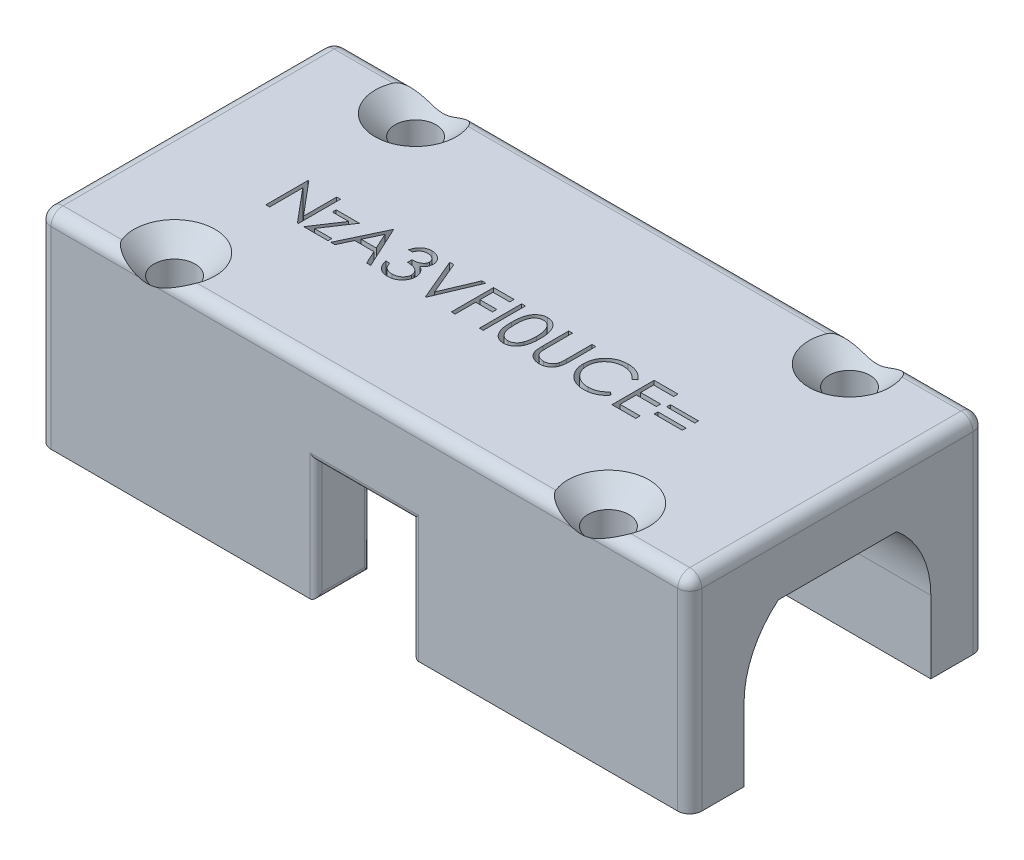
SolidWorks part; units mm, degrees
ref_plane "Alzado" through (0, 0, 0) normal (0, 0, 1) x (1, 0, 0)
ref_plane "Planta" through (0, 0, 0) normal (0, 1, 0) x (1, 0, 0)
ref_plane "Vista lateral" through (0, 0, 0) normal (1, 0, 0) x (0, 0, -1)
sketch "Croquis1" plane through (0, 0, 0) normal (0, 1, 0) x (1, 0, 0)
  line L1 (-27, 12.25) -> (27, 12.25)
  line L2 (-27, 12.25) -> (-27, -12.25)
  line L3 (-27, -12.25) -> (27, -12.25)
  line L4 (27, 12.25) -> (27, -12.25)
  line L5 (-27, 12.25) -> (27, -12.25) construction
  line L6 (-27, -12.25) -> (27, 12.25) construction
  point P0 (0, 0)
  dimension "D1" = 54
  dimension "D2" = 24.5
extrude "Saliente-Extruir1" add sketch "Croquis1" along normal blind 17
sketch "Croquis6" plane through (27, 0, 0) normal (1, 0, 0) x (0, 0, -1)
  line L0 (0, 0) -> (0, 12) construction
  line L1 (0, 12) -> (4.9054, 12)
  line L2 (0, 12) -> (-4.9054, 12)
  arc A0 (-4.9054, 12) -> (4.9054, 12) centre (0, 6) ccw
  dimension "D2" = 15.5
  dimension "D1" = 12
extrude "Cortar-Extruir3" cut sketch "Croquis6" against normal through all
sketch "Croquis7" plane through (0, 0, 12.25) normal (0, 0, 1) x (1, 0, 0)
  line L0 (0, 0) -> (0, 17) construction
  line L1 (-27, 17) -> (27, 17) construction
  line L2 (-27, 0) -> (27, 0) construction
  line L3 (-4, 10) -> (4, 10)
  line L4 (-4, 10) -> (-4, 0)
  line L5 (-4, 0) -> (4, 0)
  line L6 (4, 10) -> (4, 0)
  line L7 (-4, 10) -> (4, 0) construction
  line L8 (-4, 0) -> (4, 10) construction
  point P5 (0, 5)
  dimension "D1" = 10
  dimension "D2" = 8
extrude "Cortar-Extruir4" cut sketch "Croquis7" against normal blind 10
sketch "Croquis8" plane through (27, 0, 0) normal (1, 0, 0) x (0, 0, -1)
  line L0 (-4.9054, 0) -> (4.9054, 0) construction
  line L2 (-7.75, -6) -> (7.75, -6)
  line L3 (-7.75, -6) -> (-7.75, 6)
  line L4 (-7.75, 6) -> (7.75, 6)
  line L5 (7.75, -6) -> (7.75, 6)
  line L6 (-7.75, -6) -> (7.75, 6) construction
  line L7 (-7.75, 6) -> (7.75, -6) construction
  arc A0 (4.9054, 0) -> (4.9054, 12) centre (0, 6) ccw construction
  point P4 (0, 0)
extrude "Cortar-Extruir5" cut sketch "Croquis8" against normal through all
fillet "Redondeo1" radius 1 8 edges at (0, 17, 12.25) (-27, 17, 0) (0, 17, -12.25) (27, 17, 0) (-27, 8.5, 12.25) (-27, 8.5, -12.25) (27, 8.5, -12.25) (27, 8.5, 12.25)
sketch "Croquis9" plane through (0, 0, 0) normal (0, -1, 0) x (-1, 0, 0)
  line L0 (0, 12.25) -> (0, 0) construction
  line L1 (-26, 12.25) -> (26, 12.25) construction
  line L2 (0, 0) -> (27, 0) construction
  line L3 (27, 4.9054) -> (27, -4.9054) construction
  line L6 (26, -12.25) -> (4, -12.25) construction
  line L8 (27, -7.75) -> (27, -11.25) construction
  circle A0 centre (18, -10) radius 1
  circle A1 centre (9, -10) radius 1
  circle A2 centre (9, 10) radius 1
  circle A3 centre (18, 10) radius 1
  circle A4 centre (-9, 10) radius 1
  circle A5 centre (-18, 10) radius 1
  circle A6 centre (-9, -10) radius 1
  circle A7 centre (-18, -10) radius 1
  dimension "D1" = 2
  dimension "D2" = 2
  dimension "D3" = 2.25
  dimension "D4" = 2.25
  dimension "D5" = 9
  dimension "D6" = 9
sketch "Croquis14" plane through (0, 17, 0) normal (0, 1, 0) x (1, 0, 0)
  line L1 (0, 12.25) -> (0, 0) construction
  line L2 (0, 0) -> (-27, 0) construction
  circle A0 centre (-18, 10) radius 1.0126
  circle A1 centre (-9, 10) radius 1
  circle A2 centre (-9, -10) radius 1
  circle A3 centre (-18, -10) radius 1.0126
  circle A4 centre (9, -10) radius 1
  circle A5 centre (18, -10) radius 1.0126
  circle A6 centre (9, 10) radius 1
  circle A7 centre (18, 10) radius 1.0126
hole_wizard "Refrentado para tornillo tapón con cabeza plana de clavija de M31" positions "Croquis3D4" profile "Croquis16" countersink size "M3" standard "Ansi Metric" end condition through all
sketch3d "Croquis3D4"
  point P0 (-18, 17, -10)
  point P9 (18, 17, -10)
  point P12 (18, 17, 10)
  point P21 (-18, 17, 10)
sketch "Croquis16" plane through (-18, 17, -10) normal (1, 0, 0) x (0, 0, 1)
  line L0 (0, 0) -> (0, 17)
  line L1 (0, 17) -> (1.7, 17)
  line L2 (1.7, 17) -> (1.7, 1.66)
  line L3 (1.7, 1.66) -> (3.36, 0)
  line L5 (3.36, 0) -> (0, 0)
  line L6 (-1.7, 1.66) -> (-3.36, 0) construction
  line L11 (0, -6.35) -> (0, 107.95) construction
  dimension "Diámetro de taladro hasta el siguiente" = 3.4
  dimension "Profundidad de taladro hasta el siguiente" = 17
  dimension "Diámetro de avellanado cercano" = 6.72
  dimension "Ángulo de avellanado cercano" = 90
fillet "Fillet1" radius 0.5 9 edges at (4, 8.0759, 7.4668) (-4, 8.0759, 7.4668) (-4, 0, 10) (4, 0, 10) (4, 3, 7.75) (-4, 3, 7.75) (0, 10, 12.25) (4, 5, 12.25) (-4, 5, 12.25)
sketch "Croquis17" plane through (0, 0, -12.25) normal (0, 0, -1) x (-1, 0, 0)
  line L1 (-26, 16) -> (-26, 0) construction
  line L2 (26, 0) -> (26, 16) construction
  line L3 (0, 16) -> (0, 0) construction
  line L4 (17.2879, 16) -> (-17.2879, 16) construction
  line L6 (-26, 4.963) -> (26, 4.963) construction
sketch "Croquis18" plane through (0, 0, -12.25) normal (0, 0, -1) x (-1, 0, 0)
  line L0 (0, 16) -> (0, 0) construction
  line L5 (0, 8.8883) -> (0.5, 8.8883)
  line L7 (0, 7.8883) -> (0.5, 7.8883)
  line L8 (0.5, 8.8883) -> (0.5, 7.8883)
  line L10 (0, 8.8883) -> (-0.5, 8.8883)
  line L12 (0, 7.8883) -> (-0.5, 7.8883)
  line L13 (-0.5, 8.8883) -> (-0.5, 7.8883)
  line L14 (1.7, 8.8883) -> (1.7, 7.8883)
  line L31 (4.8, 8.8883) -> (5.3, 8.8883)
  line L33 (4.8, 7.8883) -> (5.3, 7.8883)
  line L34 (4.8, 7.8883) -> (4.3, 7.8883)
  line L35 (4.3, 8.8883) -> (4.3, 7.8883)
  line L36 (4.8, 8.8883) -> (4.3, 8.8883)
  line L43 (1.2, 10.0883) -> (1.7, 10.0883)
  line L44 (1.7, 10.0883) -> (1.7, 9.0883)
  line L45 (1.2, 9.0883) -> (1.7, 9.0883)
  line L46 (1.2, 9.0883) -> (0.7, 9.0883)
  line L47 (0.7, 10.0883) -> (0.7, 9.0883)
  line L48 (1.2, 10.0883) -> (0.7, 10.0883)
  line L49 (2.4, 10.0883) -> (2.9, 10.0883)
  line L50 (2.9, 10.0883) -> (2.9, 9.0883)
  line L51 (2.4, 9.0883) -> (2.9, 9.0883)
  line L52 (2.4, 9.0883) -> (1.9, 9.0883)
  line L53 (1.9, 10.0883) -> (1.9, 9.0883)
  line L54 (2.4, 10.0883) -> (1.9, 10.0883)
  line L55 (3.6, 10.0883) -> (4.1, 10.0883)
  line L56 (4.1, 10.0883) -> (4.1, 9.0883)
  line L57 (3.6, 9.0883) -> (4.1, 9.0883)
  line L58 (3.6, 9.0883) -> (3.1, 9.0883)
  line L59 (3.1, 10.0883) -> (3.1, 9.0883)
  line L60 (3.6, 10.0883) -> (3.1, 10.0883)
  line L79 (2.4, 11.2883) -> (2.9, 11.2883)
  line L80 (2.9, 11.2883) -> (2.9, 10.2883)
  line L81 (2.4, 10.2883) -> (2.9, 10.2883)
  line L82 (2.4, 10.2883) -> (1.9, 10.2883)
  line L83 (1.9, 11.2883) -> (1.9, 10.2883)
  line L84 (2.4, 11.2883) -> (1.9, 11.2883)
  line L115 (3.6, 12.4883) -> (4.1, 12.4883)
  line L116 (4.1, 12.4883) -> (4.1, 11.4883)
  line L117 (3.6, 11.4883) -> (4.1, 11.4883)
  line L118 (3.6, 11.4883) -> (3.1, 11.4883)
  line L119 (3.1, 12.4883) -> (3.1, 11.4883)
  line L120 (3.6, 12.4883) -> (3.1, 12.4883)
  line L194 (0.5, 10.0883) -> (0.5, 9.0883)
  line L195 (0, 9.0883) -> (0.5, 9.0883)
  line L196 (0, 9.0883) -> (-0.5, 9.0883)
  line L223 (-1.2, 8.8883) -> (-0.7, 8.8883)
  line L228 (-1.2, 8.8883) -> (-1.7, 8.8883)
  line L244 (-4.8, 7.8883) -> (-5.3, 7.8883)
  line L253 (-1.2, 10.0883) -> (-0.7, 10.0883)
  line L254 (-0.7, 10.0883) -> (-0.7, 9.0883)
  line L255 (-1.2, 9.0883) -> (-0.7, 9.0883)
  line L256 (-1.2, 9.0883) -> (-1.7, 9.0883)
  line L257 (-1.7, 10.0883) -> (-1.7, 9.0883)
  line L258 (-1.2, 10.0883) -> (-1.7, 10.0883)
  line L259 (-2.4, 10.0883) -> (-1.9, 10.0883)
  line L260 (-1.9, 10.0883) -> (-1.9, 9.0883)
  line L261 (-2.4, 9.0883) -> (-1.9, 9.0883)
  line L262 (-2.4, 9.0883) -> (-2.9, 9.0883)
  line L263 (-2.9, 10.0883) -> (-2.9, 9.0883)
  line L264 (-2.4, 10.0883) -> (-2.9, 10.0883)
  line L265 (-3.6, 10.0883) -> (-3.1, 10.0883)
  line L266 (-3.1, 10.0883) -> (-3.1, 9.0883)
  line L267 (-3.6, 9.0883) -> (-3.1, 9.0883)
  line L268 (-3.6, 9.0883) -> (-4.1, 9.0883)
  line L269 (-4.1, 10.0883) -> (-4.1, 9.0883)
  line L270 (-3.6, 10.0883) -> (-4.1, 10.0883)
  line L289 (-2.4, 11.2883) -> (-1.9, 11.2883)
  line L290 (-1.9, 11.2883) -> (-1.9, 10.2883)
  line L291 (-2.4, 10.2883) -> (-1.9, 10.2883)
  line L292 (-2.4, 10.2883) -> (-2.9, 10.2883)
  line L293 (-2.9, 11.2883) -> (-2.9, 10.2883)
  line L294 (-2.4, 11.2883) -> (-2.9, 11.2883)
  line L325 (-3.6, 12.4883) -> (-3.1, 12.4883)
  line L326 (-3.1, 12.4883) -> (-3.1, 11.4883)
  line L327 (-3.6, 11.4883) -> (-3.1, 11.4883)
  line L328 (-3.6, 11.4883) -> (-4.1, 11.4883)
  line L329 (-4.1, 12.4883) -> (-4.1, 11.4883)
  line L330 (-3.6, 12.4883) -> (-4.1, 12.4883)
  line L403 (0, 10.0883) -> (0.5, 10.0883)
  line L404 (0.5, 10.0883) -> (0.5, 9.0883)
  line L405 (0, 9.0883) -> (0.5, 9.0883)
  line L406 (0, 9.0883) -> (-0.5, 9.0883)
  line L407 (-0.5, 10.0883) -> (-0.5, 9.0883)
  line L408 (0, 10.0883) -> (-0.5, 10.0883)
  line L434 (1.2, 8.8883) -> (1.7, 8.8883)
  line L435 (1.7, 8.8883) -> (1.7, 7.8883)
  line L436 (1.2, 7.8883) -> (1.7, 7.8883)
  line L437 (1.2, 7.8883) -> (0.7, 7.8883)
  line L438 (0.7, 8.8883) -> (0.7, 7.8883)
  line L439 (1.2, 8.8883) -> (0.7, 8.8883)
  line L440 (3.1, 8.8883) -> (3.1, 7.8883)
  line L447 (4.3, 8.8883) -> (4.3, 7.8883)
  line L448 (3.6, 8.8883) -> (4.1, 8.8883)
  line L449 (4.1, 8.8883) -> (4.1, 7.8883)
  line L450 (3.6, 7.8883) -> (4.1, 7.8883)
  line L451 (3.6, 7.8883) -> (3.1, 7.8883)
  line L452 (3.1, 8.8883) -> (3.1, 7.8883)
  line L453 (3.6, 8.8883) -> (3.1, 8.8883)
  line L455 (4.8, 8.8883) -> (5.3, 8.8883)
  line L456 (5.3, 8.8883) -> (5.3, 7.8883)
  line L457 (4.8, 7.8883) -> (5.3, 7.8883)
  line L458 (4.8, 7.8883) -> (4.3, 7.8883)
  line L459 (4.3, 8.8883) -> (4.3, 7.8883)
  line L460 (4.8, 8.8883) -> (4.3, 8.8883)
  line L468 (1.9, 7.6883) -> (1.9, 6.6883)
  line L469 (1.2, 7.6883) -> (1.7, 7.6883)
  line L470 (1.7, 7.6883) -> (1.7, 6.6883)
  line L471 (1.2, 6.6883) -> (1.7, 6.6883)
  line L472 (1.2, 6.6883) -> (0.7, 6.6883)
  line L473 (0.7, 7.6883) -> (0.7, 6.6883)
  line L474 (1.2, 7.6883) -> (0.7, 7.6883)
  line L475 (3.1, 7.6883) -> (3.1, 6.6883)
  line L476 (2.4, 7.6883) -> (2.9, 7.6883)
  line L477 (2.9, 7.6883) -> (2.9, 6.6883)
  line L478 (2.4, 6.6883) -> (2.9, 6.6883)
  line L479 (2.4, 6.6883) -> (1.9, 6.6883)
  line L480 (1.9, 7.6883) -> (1.9, 6.6883)
  line L481 (2.4, 7.6883) -> (1.9, 7.6883)
  line L482 (4.3, 7.6883) -> (4.3, 6.6883)
  line L483 (3.6, 7.6883) -> (4.1, 7.6883)
  line L484 (4.1, 7.6883) -> (4.1, 6.6883)
  line L485 (3.6, 6.6883) -> (4.1, 6.6883)
  line L486 (3.6, 6.6883) -> (3.1, 6.6883)
  line L487 (3.1, 7.6883) -> (3.1, 6.6883)
  line L488 (3.6, 7.6883) -> (3.1, 7.6883)
  line L489 (5.5, 7.6883) -> (5.5, 6.6883)
  line L490 (4.8, 7.6883) -> (5.3, 7.6883)
  line L491 (5.3, 7.6883) -> (5.3, 6.6883)
  line L492 (4.8, 6.6883) -> (5.3, 6.6883)
  line L493 (4.8, 6.6883) -> (4.3, 6.6883)
  line L494 (4.3, 7.6883) -> (4.3, 6.6883)
  line L495 (4.8, 7.6883) -> (4.3, 7.6883)
  line L497 (6, 7.6883) -> (6.5, 7.6883)
  line L498 (6.5, 7.6883) -> (6.5, 6.6883)
  line L499 (6, 6.6883) -> (6.5, 6.6883)
  line L500 (6, 6.6883) -> (5.5, 6.6883)
  line L501 (5.5, 7.6883) -> (5.5, 6.6883)
  line L502 (6, 7.6883) -> (5.5, 7.6883)
  line L503 (1.9, 6.4883) -> (1.9, 5.4883)
  line L504 (1.2, 6.4883) -> (1.7, 6.4883)
  line L505 (1.7, 6.4883) -> (1.7, 5.4883)
  line L506 (1.2, 5.4883) -> (1.7, 5.4883)
  line L507 (1.2, 5.4883) -> (0.7, 5.4883)
  line L508 (0.7, 6.4883) -> (0.7, 5.4883)
  line L509 (1.2, 6.4883) -> (0.7, 6.4883)
  line L510 (3.1, 6.4883) -> (3.1, 5.4883)
  line L511 (2.4, 6.4883) -> (2.9, 6.4883)
  line L512 (2.9, 6.4883) -> (2.9, 5.4883)
  line L513 (2.4, 5.4883) -> (2.9, 5.4883)
  line L514 (2.4, 5.4883) -> (1.9, 5.4883)
  line L515 (1.9, 6.4883) -> (1.9, 5.4883)
  line L516 (2.4, 6.4883) -> (1.9, 6.4883)
  line L518 (3.6, 6.4883) -> (4.1, 6.4883)
  line L519 (4.1, 6.4883) -> (4.1, 5.4883)
  line L520 (3.6, 5.4883) -> (4.1, 5.4883)
  line L521 (3.6, 5.4883) -> (3.1, 5.4883)
  line L522 (3.1, 6.4883) -> (3.1, 5.4883)
  line L523 (3.6, 6.4883) -> (3.1, 6.4883)
  line L524 (5.5, 6.4883) -> (5.5, 5.4883)
  line L532 (6, 6.4883) -> (6.5, 6.4883)
  line L533 (6.5, 6.4883) -> (6.5, 5.4883)
  line L534 (6, 5.4883) -> (6.5, 5.4883)
  line L535 (6, 5.4883) -> (5.5, 5.4883)
  line L536 (5.5, 6.4883) -> (5.5, 5.4883)
  line L537 (6, 6.4883) -> (5.5, 6.4883)
  line L538 (1.9, 5.2883) -> (1.9, 4.2883)
  line L539 (1.2, 5.2883) -> (1.7, 5.2883)
  line L540 (1.7, 5.2883) -> (1.7, 4.2883)
  line L541 (1.2, 4.2883) -> (1.7, 4.2883)
  line L542 (1.2, 4.2883) -> (0.7, 4.2883)
  line L543 (0.7, 5.2883) -> (0.7, 4.2883)
  line L544 (1.2, 5.2883) -> (0.7, 5.2883)
  line L545 (3.1, 5.2883) -> (3.1, 4.2883)
  line L546 (2.4, 5.2883) -> (2.9, 5.2883)
  line L547 (2.9, 5.2883) -> (2.9, 4.2883)
  line L548 (2.4, 4.2883) -> (2.9, 4.2883)
  line L549 (2.4, 4.2883) -> (1.9, 4.2883)
  line L550 (1.9, 5.2883) -> (1.9, 4.2883)
  line L551 (2.4, 5.2883) -> (1.9, 5.2883)
  line L553 (3.6, 5.2883) -> (4.1, 5.2883)
  line L554 (4.1, 5.2883) -> (4.1, 4.2883)
  line L555 (3.6, 4.2883) -> (4.1, 4.2883)
  line L556 (3.6, 4.2883) -> (3.1, 4.2883)
  line L557 (3.1, 5.2883) -> (3.1, 4.2883)
  line L558 (3.6, 5.2883) -> (3.1, 5.2883)
  line L559 (5.5, 5.2883) -> (5.5, 4.2883)
  line L567 (6, 5.2883) -> (6.5, 5.2883)
  line L568 (6.5, 5.2883) -> (6.5, 4.2883)
  line L569 (6, 4.2883) -> (6.5, 4.2883)
  line L570 (6, 4.2883) -> (5.5, 4.2883)
  line L571 (5.5, 5.2883) -> (5.5, 4.2883)
  line L572 (6, 5.2883) -> (5.5, 5.2883)
  line L580 (3.1, 4.0883) -> (3.1, 3.0883)
  line L588 (3.6, 4.0883) -> (4.1, 4.0883)
  line L589 (4.1, 4.0883) -> (4.1, 3.0883)
  line L590 (3.6, 3.0883) -> (4.1, 3.0883)
  line L591 (3.6, 3.0883) -> (3.1, 3.0883)
  line L592 (3.1, 4.0883) -> (3.1, 3.0883)
  line L593 (3.6, 4.0883) -> (3.1, 4.0883)
  line L608 (1.9, 2.8883) -> (1.9, 1.8883)
  line L609 (1.2, 2.8883) -> (1.7, 2.8883)
  line L610 (1.7, 2.8883) -> (1.7, 1.8883)
  line L611 (1.2, 1.8883) -> (1.7, 1.8883)
  line L612 (1.2, 1.8883) -> (0.7, 1.8883)
  line L613 (0.7, 2.8883) -> (0.7, 1.8883)
  line L614 (1.2, 2.8883) -> (0.7, 2.8883)
  line L616 (2.4, 2.8883) -> (2.9, 2.8883)
  line L617 (2.9, 2.8883) -> (2.9, 1.8883)
  line L618 (2.4, 1.8883) -> (2.9, 1.8883)
  line L619 (2.4, 1.8883) -> (1.9, 1.8883)
  line L620 (1.9, 2.8883) -> (1.9, 1.8883)
  line L621 (2.4, 2.8883) -> (1.9, 2.8883)
  line L643 (0.7, 7.6883) -> (0.7, 6.6883)
  line L650 (0.7, 6.4883) -> (0.7, 5.4883)
  line L657 (0.7, 5.2883) -> (0.7, 4.2883)
  line L671 (0.7, 2.8883) -> (0.7, 1.8883)
  line L678 (-1.2, 8.8883) -> (-0.7, 8.8883)
  line L679 (-0.7, 8.8883) -> (-0.7, 7.8883)
  line L680 (-1.2, 7.8883) -> (-0.7, 7.8883)
  line L681 (-1.2, 7.8883) -> (-1.7, 7.8883)
  line L682 (-1.7, 8.8883) -> (-1.7, 7.8883)
  line L683 (-1.2, 8.8883) -> (-1.7, 8.8883)
  line L690 (-3.6, 8.8883) -> (-3.1, 8.8883)
  line L691 (-3.1, 8.8883) -> (-3.1, 7.8883)
  line L692 (-3.6, 7.8883) -> (-3.1, 7.8883)
  line L693 (-3.6, 7.8883) -> (-4.1, 7.8883)
  line L694 (-4.1, 8.8883) -> (-4.1, 7.8883)
  line L695 (-3.6, 8.8883) -> (-4.1, 8.8883)
  line L696 (-4.8, 8.8883) -> (-4.3, 8.8883)
  line L697 (-4.3, 8.8883) -> (-4.3, 7.8883)
  line L698 (-4.8, 7.8883) -> (-4.3, 7.8883)
  line L699 (-4.8, 7.8883) -> (-5.3, 7.8883)
  line L700 (-5.3, 8.8883) -> (-5.3, 7.8883)
  line L701 (-4.8, 8.8883) -> (-5.3, 8.8883)
  line L708 (-1.2, 7.6883) -> (-0.7, 7.6883)
  line L709 (-0.7, 7.6883) -> (-0.7, 6.6883)
  line L710 (-1.2, 6.6883) -> (-0.7, 6.6883)
  line L711 (-1.2, 6.6883) -> (-1.7, 6.6883)
  line L712 (-1.7, 7.6883) -> (-1.7, 6.6883)
  line L713 (-1.2, 7.6883) -> (-1.7, 7.6883)
  line L714 (-2.4, 7.6883) -> (-1.9, 7.6883)
  line L715 (-1.9, 7.6883) -> (-1.9, 6.6883)
  line L716 (-2.4, 6.6883) -> (-1.9, 6.6883)
  line L717 (-2.4, 6.6883) -> (-2.9, 6.6883)
  line L718 (-2.9, 7.6883) -> (-2.9, 6.6883)
  line L719 (-2.4, 7.6883) -> (-2.9, 7.6883)
  line L720 (-3.6, 7.6883) -> (-3.1, 7.6883)
  line L721 (-3.1, 7.6883) -> (-3.1, 6.6883)
  line L722 (-3.6, 6.6883) -> (-3.1, 6.6883)
  line L723 (-3.6, 6.6883) -> (-4.1, 6.6883)
  line L724 (-4.1, 7.6883) -> (-4.1, 6.6883)
  line L725 (-3.6, 7.6883) -> (-4.1, 7.6883)
  line L726 (-4.8, 7.6883) -> (-4.3, 7.6883)
  line L727 (-4.3, 7.6883) -> (-4.3, 6.6883)
  line L728 (-4.8, 6.6883) -> (-4.3, 6.6883)
  line L729 (-4.8, 6.6883) -> (-5.3, 6.6883)
  line L730 (-5.3, 7.6883) -> (-5.3, 6.6883)
  line L731 (-4.8, 7.6883) -> (-5.3, 7.6883)
  line L732 (-6, 7.6883) -> (-5.5, 7.6883)
  line L733 (-5.5, 7.6883) -> (-5.5, 6.6883)
  line L734 (-6, 6.6883) -> (-5.5, 6.6883)
  line L735 (-6, 6.6883) -> (-6.5, 6.6883)
  line L736 (-6.5, 7.6883) -> (-6.5, 6.6883)
  line L737 (-6, 7.6883) -> (-6.5, 7.6883)
  line L738 (-1.2, 6.4883) -> (-0.7, 6.4883)
  line L739 (-0.7, 6.4883) -> (-0.7, 5.4883)
  line L740 (-1.2, 5.4883) -> (-0.7, 5.4883)
  line L741 (-1.2, 5.4883) -> (-1.7, 5.4883)
  line L742 (-1.7, 6.4883) -> (-1.7, 5.4883)
  line L743 (-1.2, 6.4883) -> (-1.7, 6.4883)
  line L744 (-2.4, 6.4883) -> (-1.9, 6.4883)
  line L745 (-1.9, 6.4883) -> (-1.9, 5.4883)
  line L746 (-2.4, 5.4883) -> (-1.9, 5.4883)
  line L747 (-2.4, 5.4883) -> (-2.9, 5.4883)
  line L748 (-2.9, 6.4883) -> (-2.9, 5.4883)
  line L749 (-2.4, 6.4883) -> (-2.9, 6.4883)
  line L750 (-3.6, 6.4883) -> (-3.1, 6.4883)
  line L751 (-3.1, 6.4883) -> (-3.1, 5.4883)
  line L752 (-3.6, 5.4883) -> (-3.1, 5.4883)
  line L753 (-3.6, 5.4883) -> (-4.1, 5.4883)
  line L754 (-4.1, 6.4883) -> (-4.1, 5.4883)
  line L755 (-3.6, 6.4883) -> (-4.1, 6.4883)
  line L762 (-6, 6.4883) -> (-5.5, 6.4883)
  line L763 (-5.5, 6.4883) -> (-5.5, 5.4883)
  line L764 (-6, 5.4883) -> (-5.5, 5.4883)
  line L765 (-6, 5.4883) -> (-6.5, 5.4883)
  line L766 (-6.5, 6.4883) -> (-6.5, 5.4883)
  line L767 (-6, 6.4883) -> (-6.5, 6.4883)
  line L768 (-1.2, 5.2883) -> (-0.7, 5.2883)
  line L769 (-0.7, 5.2883) -> (-0.7, 4.2883)
  line L770 (-1.2, 4.2883) -> (-0.7, 4.2883)
  line L771 (-1.2, 4.2883) -> (-1.7, 4.2883)
  line L772 (-1.7, 5.2883) -> (-1.7, 4.2883)
  line L773 (-1.2, 5.2883) -> (-1.7, 5.2883)
  line L774 (-2.4, 5.2883) -> (-1.9, 5.2883)
  line L775 (-1.9, 5.2883) -> (-1.9, 4.2883)
  line L776 (-2.4, 4.2883) -> (-1.9, 4.2883)
  line L777 (-2.4, 4.2883) -> (-2.9, 4.2883)
  line L778 (-2.9, 5.2883) -> (-2.9, 4.2883)
  line L779 (-2.4, 5.2883) -> (-2.9, 5.2883)
  line L780 (-3.6, 5.2883) -> (-3.1, 5.2883)
  line L781 (-3.1, 5.2883) -> (-3.1, 4.2883)
  line L782 (-3.6, 4.2883) -> (-3.1, 4.2883)
  line L783 (-3.6, 4.2883) -> (-4.1, 4.2883)
  line L784 (-4.1, 5.2883) -> (-4.1, 4.2883)
  line L785 (-3.6, 5.2883) -> (-4.1, 5.2883)
  line L792 (-6, 5.2883) -> (-5.5, 5.2883)
  line L793 (-5.5, 5.2883) -> (-5.5, 4.2883)
  line L794 (-6, 4.2883) -> (-5.5, 4.2883)
  line L795 (-6, 4.2883) -> (-6.5, 4.2883)
  line L796 (-6.5, 5.2883) -> (-6.5, 4.2883)
  line L797 (-6, 5.2883) -> (-6.5, 5.2883)
  line L810 (-3.6, 4.0883) -> (-3.1, 4.0883)
  line L811 (-3.1, 4.0883) -> (-3.1, 3.0883)
  line L812 (-3.6, 3.0883) -> (-3.1, 3.0883)
  line L813 (-3.6, 3.0883) -> (-4.1, 3.0883)
  line L814 (-4.1, 4.0883) -> (-4.1, 3.0883)
  line L815 (-3.6, 4.0883) -> (-4.1, 4.0883)
  line L828 (-1.2, 2.8883) -> (-0.7, 2.8883)
  line L829 (-0.7, 2.8883) -> (-0.7, 1.8883)
  line L830 (-1.2, 1.8883) -> (-0.7, 1.8883)
  line L831 (-1.2, 1.8883) -> (-1.7, 1.8883)
  line L832 (-1.7, 2.8883) -> (-1.7, 1.8883)
  line L833 (-1.2, 2.8883) -> (-1.7, 2.8883)
  line L834 (-2.4, 2.8883) -> (-1.9, 2.8883)
  line L835 (-1.9, 2.8883) -> (-1.9, 1.8883)
  line L836 (-2.4, 1.8883) -> (-1.9, 1.8883)
  line L837 (-2.4, 1.8883) -> (-2.9, 1.8883)
  line L838 (-2.9, 2.8883) -> (-2.9, 1.8883)
  line L839 (-2.4, 2.8883) -> (-2.9, 2.8883)
  line L858 (0, 7.6883) -> (0.5, 7.6883)
  line L859 (0.5, 7.6883) -> (0.5, 6.6883)
  line L860 (0, 6.6883) -> (0.5, 6.6883)
  line L861 (0, 6.6883) -> (-0.5, 6.6883)
  line L862 (-0.5, 7.6883) -> (-0.5, 6.6883)
  line L863 (0, 7.6883) -> (-0.5, 7.6883)
  line L864 (0, 6.4883) -> (0.5, 6.4883)
  line L865 (0.5, 6.4883) -> (0.5, 5.4883)
  line L866 (0, 5.4883) -> (0.5, 5.4883)
  line L867 (0, 5.4883) -> (-0.5, 5.4883)
  line L868 (-0.5, 6.4883) -> (-0.5, 5.4883)
  line L869 (0, 6.4883) -> (-0.5, 6.4883)
  line L870 (0, 5.2883) -> (0.5, 5.2883)
  line L871 (0.5, 5.2883) -> (0.5, 4.2883)
  line L872 (0, 4.2883) -> (0.5, 4.2883)
  line L873 (0, 4.2883) -> (-0.5, 4.2883)
  line L874 (-0.5, 5.2883) -> (-0.5, 4.2883)
  line L875 (0, 5.2883) -> (-0.5, 5.2883)
  line L888 (2.4, 8.8883) -> (2.9, 8.8883) [skipped]
  line L889 (2.4, 8.8883) -> (2.9, 8.8883) [skipped]
  line L890 (2.4, 8.8883) -> (1.9, 8.8883) [skipped]
  line L891 (1.9, 8.8883) -> (1.9, 7.8883) [skipped]
  line L893 (2.4, 8.8883) -> (1.9, 8.8883) [skipped]
  line L894 (1.9, 8.8883) -> (1.9, 7.8883) [skipped]
  line L895 (2.4, 7.8883) -> (2.9, 7.8883) [skipped]
  line L896 (2.4, 7.8883) -> (2.9, 7.8883) [skipped]
  line L897 (2.4, 7.8883) -> (1.9, 7.8883) [skipped]
  line L898 (2.4, 7.8883) -> (1.9, 7.8883) [skipped]
  line L899 (2.9, 8.8883) -> (2.9, 7.8883) [skipped]
  line L900 (5.5, 8.8883) -> (5.5, 7.8883) [skipped]
  line L901 (5.3, 8.8883) -> (5.3, 7.8883) [skipped]
  line L903 (5.5, 8.8883) -> (5.5, 7.8883) [skipped]
  line L904 (6, 8.8883) -> (5.5, 8.8883) [skipped]
  line L905 (6, 8.8883) -> (6.5, 8.8883) [skipped]
  line L906 (6, 8.8883) -> (6.5, 8.8883) [skipped]
  line L907 (6, 8.8883) -> (5.5, 8.8883) [skipped]
  line L908 (6, 7.8883) -> (5.5, 7.8883) [skipped]
  line L909 (6, 7.8883) -> (6.5, 7.8883) [skipped]
  line L910 (6, 7.8883) -> (5.5, 7.8883) [skipped]
  line L911 (6, 7.8883) -> (6.5, 7.8883) [skipped]
  line L912 (6.5, 8.8883) -> (6.5, 7.8883) [skipped]
  line L914 (6.5, 8.8883) -> (6.5, 7.8883) [skipped]
  line L916 (4.8, 9.0883) -> (5.3, 9.0883) [skipped]
  line L917 (4.8, 9.0883) -> (4.3, 9.0883) [skipped]
  line L918 (4.8, 10.0883) -> (4.3, 10.0883) [skipped]
  line L919 (4.3, 10.0883) -> (4.3, 9.0883) [skipped]
  line L920 (4.8, 10.0883) -> (5.3, 10.0883) [skipped]
  line L921 (6, 10.0883) -> (5.5, 10.0883) [skipped]
  line L922 (5.3, 10.0883) -> (5.3, 9.0883) [skipped]
  line L923 (5.5, 10.0883) -> (5.5, 9.0883) [skipped]
  line L924 (6, 9.0883) -> (5.5, 9.0883) [skipped]
  line L925 (6.5, 10.0883) -> (6.5, 9.0883) [skipped]
  line L926 (6, 9.0883) -> (6.5, 9.0883) [skipped]
  line L927 (6, 10.0883) -> (6.5, 10.0883) [skipped]
  line L928 (4.8, 11.2883) -> (5.3, 11.2883) [skipped]
  line L929 (4.8, 11.2883) -> (4.3, 11.2883) [skipped]
  line L930 (4.3, 11.2883) -> (4.3, 10.2883) [skipped]
  line L931 (4.8, 10.2883) -> (4.3, 10.2883) [skipped]
  line L932 (4.8, 10.2883) -> (5.3, 10.2883) [skipped]
  line L933 (5.3, 11.2883) -> (5.3, 10.2883) [skipped]
  line L934 (5.5, 11.2883) -> (5.5, 10.2883) [skipped]
  line L935 (6, 11.2883) -> (6.5, 11.2883) [skipped]
  line L936 (6, 11.2883) -> (5.5, 11.2883) [skipped]
  line L937 (6.5, 11.2883) -> (6.5, 10.2883) [skipped]
  line L938 (6, 10.2883) -> (6.5, 10.2883) [skipped]
  line L939 (6, 10.2883) -> (5.5, 10.2883) [skipped]
  line L940 (3.6, 10.2883) -> (3.1, 10.2883) [skipped]
  line L941 (3.6, 11.2883) -> (4.1, 11.2883) [skipped]
  line L942 (3.6, 11.2883) -> (3.1, 11.2883) [skipped]
  line L943 (3.1, 11.2883) -> (3.1, 10.2883) [skipped]
  line L944 (4.1, 11.2883) -> (4.1, 10.2883) [skipped]
  line L945 (3.6, 10.2883) -> (4.1, 10.2883) [skipped]
  line L946 (2.9, 12.4883) -> (2.9, 11.4883) [skipped]
  line L947 (2.4, 11.4883) -> (1.9, 11.4883) [skipped]
  line L948 (2.4, 11.4883) -> (2.9, 11.4883) [skipped]
  line L949 (2.4, 12.4883) -> (2.9, 12.4883) [skipped]
  line L950 (2.4, 12.4883) -> (1.9, 12.4883) [skipped]
  line L951 (2.4, 12.6883) -> (2.9, 12.6883) [skipped]
  line L952 (2.4, 12.6883) -> (1.9, 12.6883) [skipped]
  line L953 (4.1, 13.6883) -> (4.1, 12.6883) [skipped]
  line L954 (3.1, 13.6883) -> (3.1, 12.6883) [skipped]
  line L955 (2.9, 13.6883) -> (2.9, 12.6883) [skipped]
  line L956 (3.6, 12.6883) -> (3.1, 12.6883) [skipped]
  line L957 (3.6, 12.6883) -> (4.1, 12.6883) [skipped]
  line L958 (4.8, 12.6883) -> (4.3, 12.6883) [skipped]
  line L959 (4.8, 12.6883) -> (5.3, 12.6883) [skipped]
  line L960 (4.8, 12.4883) -> (5.3, 12.4883) [skipped]
  line L961 (4.8, 12.4883) -> (4.3, 12.4883) [skipped]
  line L962 (4.3, 12.4883) -> (4.3, 11.4883) [skipped]
  line L963 (4.8, 11.4883) -> (5.3, 11.4883) [skipped]
  line L964 (5.3, 12.4883) -> (5.3, 11.4883) [skipped]
  line L965 (4.8, 11.4883) -> (4.3, 11.4883) [skipped]
  line L966 (5.5, 12.4883) -> (5.5, 11.4883) [skipped]
  line L967 (6, 12.4883) -> (6.5, 12.4883) [skipped]
  line L968 (6, 12.4883) -> (5.5, 12.4883) [skipped]
  line L969 (6, 11.4883) -> (5.5, 11.4883) [skipped]
  line L970 (6, 11.4883) -> (6.5, 11.4883) [skipped]
  line L971 (6.5, 12.4883) -> (6.5, 11.4883) [skipped]
  line L972 (5.5, 13.6883) -> (5.5, 12.6883) [skipped]
  line L973 (5.3, 13.6883) -> (5.3, 12.6883) [skipped]
  line L974 (4.3, 13.6883) -> (4.3, 12.6883) [skipped]
  line L975 (4.8, 13.6883) -> (4.3, 13.6883) [skipped]
  line L976 (4.8, 13.6883) -> (5.3, 13.6883) [skipped]
  line L977 (4.8, 13.8883) -> (4.3, 13.8883) [skipped]
  line L978 (4.3, 14.8883) -> (4.3, 13.8883) [skipped]
  line L979 (2.4, 14.8883) -> (2.9, 14.8883) [skipped]
  line L980 (2.4, 14.8883) -> (1.9, 14.8883) [skipped]
  line L981 (1.2, 12.4883) -> (1.7, 12.4883) [skipped]
  line L982 (1.7, 12.4883) -> (1.7, 11.4883) [skipped]
  line L983 (1.9, 12.4883) -> (1.9, 11.4883) [skipped]
  line L984 (2.4, 13.6883) -> (1.9, 13.6883) [skipped]
  line L985 (6, 12.6883) -> (6.5, 12.6883) [skipped]
  line L986 (6, 12.6883) -> (5.5, 12.6883) [skipped]
  line L987 (6.5, 13.6883) -> (6.5, 12.6883) [skipped]
  line L988 (6.5, 14.8883) -> (6.5, 13.8883) [skipped]
  line L989 (6, 13.6883) -> (6.5, 13.6883) [skipped]
  line L990 (6, 13.6883) -> (5.5, 13.6883) [skipped]
  line L991 (6, 13.8883) -> (6.5, 13.8883) [skipped]
  line L992 (6, 13.8883) -> (5.5, 13.8883) [skipped]
  line L993 (5.5, 14.8883) -> (5.5, 13.8883) [skipped]
  line L994 (5.3, 14.8883) -> (5.3, 13.8883) [skipped]
  line L995 (6, 14.8883) -> (5.5, 14.8883) [skipped]
  line L996 (4.8, 14.8883) -> (5.3, 14.8883) [skipped]
  line L997 (4.8, 14.8883) -> (4.3, 14.8883) [skipped]
  line L998 (3.6, 14.8883) -> (4.1, 14.8883) [skipped]
  line L999 (3.6, 14.8883) -> (3.1, 14.8883) [skipped]
  line L1000 (3.1, 14.8883) -> (3.1, 13.8883) [skipped]
  line L1001 (2.9, 14.8883) -> (2.9, 13.8883) [skipped]
  line L1002 (3.6, 13.6883) -> (3.1, 13.6883) [skipped]
  line L1003 (2.4, 13.8883) -> (2.9, 13.8883) [skipped]
  line L1004 (2.4, 13.6883) -> (2.9, 13.6883) [skipped]
  line L1005 (1.9, 14.8883) -> (1.9, 13.8883) [skipped]
  line L1006 (2.4, 13.8883) -> (1.9, 13.8883) [skipped]
  line L1007 (1.9, 13.6883) -> (1.9, 12.6883) [skipped]
  line L1008 (3.6, 13.8883) -> (3.1, 13.8883) [skipped]
  line L1009 (3.6, 13.8883) -> (4.1, 13.8883) [skipped]
  line L1010 (3.6, 13.6883) -> (4.1, 13.6883) [skipped]
  line L1011 (4.1, 14.8883) -> (4.1, 13.8883) [skipped]
  line L1012 (4.8, 13.8883) -> (5.3, 13.8883) [skipped]
  line L1013 (6, 14.8883) -> (6.5, 14.8883) [skipped]
  line L1014 (1.2, 11.2883) -> (1.7, 11.2883) [skipped]
  line L1015 (1.2, 11.4883) -> (1.7, 11.4883) [skipped]
  line L1016 (1.2, 11.4883) -> (0.7, 11.4883) [skipped]
  line L1017 (0.5, 11.2883) -> (0.5, 10.2883) [skipped]
  line L1018 (0.5, 11.2883) -> (0.5, 10.2883) [skipped]
  line L1019 (-0.5, 11.2883) -> (-0.5, 10.2883) [skipped]
  line L1020 (-0.5, 11.2883) -> (-0.5, 10.2883) [skipped]
  line L1021 (-0.7, 11.2883) -> (-0.7, 10.2883) [skipped]
  line L1022 (-1.2, 11.2883) -> (-0.7, 11.2883) [skipped]
  line L1023 (0.7, 11.2883) -> (0.7, 10.2883) [skipped]
  line L1024 (0, 10.2883) -> (0.5, 10.2883) [skipped]
  line L1025 (1.2, 10.2883) -> (0.7, 10.2883) [skipped]
  line L1026 (1.2, 10.2883) -> (1.7, 10.2883) [skipped]
  line L1027 (1.7, 11.2883) -> (1.7, 10.2883) [skipped]
  line L1028 (0.5, 12.4883) -> (0.5, 11.4883) [skipped]
  line L1029 (0, 11.4883) -> (0.5, 11.4883) [skipped]
  line L1030 (0.5, 12.4883) -> (0.5, 11.4883) [skipped]
  line L1031 (0.7, 12.4883) -> (0.7, 11.4883) [skipped]
  line L1032 (1.2, 12.4883) -> (0.7, 12.4883) [skipped]
  line L1033 (1.2, 12.6883) -> (0.7, 12.6883) [skipped]
  line L1034 (0.5, 13.6883) -> (0.5, 12.6883) [skipped]
  line L1035 (0, 13.8883) -> (-0.5, 13.8883) [skipped]
  line L1036 (0, 13.8883) -> (0.5, 13.8883) [skipped]
  line L1037 (0, 13.8883) -> (0.5, 13.8883) [skipped]
  line L1038 (0, 13.8883) -> (-0.5, 13.8883) [skipped]
  line L1039 (-0.5, 14.8883) -> (-0.5, 13.8883) [skipped]
  line L1040 (-1.2, 14.8883) -> (-1.7, 14.8883) [skipped]
  line L1041 (-1.2, 14.8883) -> (-0.7, 14.8883) [skipped]
  line L1042 (-1.2, 11.4883) -> (-0.7, 11.4883) [skipped]
  line L1043 (-1.2, 11.4883) -> (-1.7, 11.4883) [skipped]
  line L1044 (-1.2, 11.2883) -> (-1.7, 11.2883) [skipped]
  line L1045 (-1.2, 10.2883) -> (-1.7, 10.2883) [skipped]
  line L1046 (-1.2, 10.2883) -> (-0.7, 10.2883) [skipped]
  line L1047 (0, 10.2883) -> (0.5, 10.2883) [skipped]
  line L1048 (0, 10.2883) -> (-0.5, 10.2883) [skipped]
  line L1049 (0, 10.2883) -> (-0.5, 10.2883) [skipped]
  line L1050 (0, 11.4883) -> (-0.5, 11.4883) [skipped]
  line L1051 (0, 11.4883) -> (0.5, 11.4883) [skipped]
  line L1052 (0, 11.4883) -> (-0.5, 11.4883) [skipped]
  line L1053 (0, 11.2883) -> (0.5, 11.2883) [skipped]
  line L1054 (1.2, 11.2883) -> (0.7, 11.2883) [skipped]
  line L1055 (0, 11.2883) -> (0.5, 11.2883) [skipped]
  line L1056 (0, 11.2883) -> (-0.5, 11.2883) [skipped]
  line L1057 (0, 11.2883) -> (-0.5, 11.2883) [skipped]
  line L1058 (-0.5, 12.4883) -> (-0.5, 11.4883) [skipped]
  line L1059 (-0.7, 12.4883) -> (-0.7, 11.4883) [skipped]
  line L1060 (-0.5, 12.4883) -> (-0.5, 11.4883) [skipped]
  line L1061 (1.2, 13.8883) -> (1.7, 13.8883) [skipped]
  line L1062 (1.2, 13.8883) -> (0.7, 13.8883) [skipped]
  line L1063 (1.2, 14.8883) -> (1.7, 14.8883) [skipped]
  line L1064 (1.2, 14.8883) -> (0.7, 14.8883) [skipped]
  line L1065 (0.5, 14.8883) -> (0.5, 13.8883) [skipped]
  line L1066 (0, 14.8883) -> (0.5, 14.8883) [skipped]
  line L1067 (0, 14.8883) -> (-0.5, 14.8883) [skipped]
  line L1068 (-0.7, 14.8883) -> (-0.7, 13.8883) [skipped]
  line L1069 (-0.5, 14.8883) -> (-0.5, 13.8883) [skipped]
  line L1070 (-0.7, 13.6883) -> (-0.7, 12.6883) [skipped]
  line L1071 (-1.2, 13.6883) -> (-0.7, 13.6883) [skipped]
  line L1072 (-1.2, 13.8883) -> (-0.7, 13.8883) [skipped]
  line L1073 (-1.2, 13.6883) -> (-1.7, 13.6883) [skipped]
  line L1074 (-1.7, 14.8883) -> (-1.7, 13.8883) [skipped]
  line L1075 (-1.2, 12.6883) -> (-1.7, 12.6883) [skipped]
  line L1076 (-1.2, 12.6883) -> (-0.7, 12.6883) [skipped]
  line L1077 (-1.2, 12.4883) -> (-0.7, 12.4883) [skipped]
  line L1078 (0, 12.6883) -> (-0.5, 12.6883) [skipped]
  line L1079 (0, 12.4883) -> (0.5, 12.4883) [skipped]
  line L1080 (0, 12.6883) -> (0.5, 12.6883) [skipped]
  line L1081 (0, 12.6883) -> (0.5, 12.6883) [skipped]
  line L1082 (0, 12.4883) -> (-0.5, 12.4883) [skipped]
  line L1083 (0, 12.4883) -> (-0.5, 12.4883) [skipped]
  line L1084 (0, 12.4883) -> (0.5, 12.4883) [skipped]
  line L1085 (0, 12.6883) -> (-0.5, 12.6883) [skipped]
  line L1086 (-0.5, 13.6883) -> (-0.5, 12.6883) [skipped]
  line L1087 (-0.5, 13.6883) -> (-0.5, 12.6883) [skipped]
  line L1088 (0, 13.6883) -> (-0.5, 13.6883) [skipped]
  line L1089 (0, 13.6883) -> (0.5, 13.6883) [skipped]
  line L1090 (0, 13.6883) -> (0.5, 13.6883) [skipped]
  line L1091 (0, 13.6883) -> (-0.5, 13.6883) [skipped]
  line L1092 (0.7, 13.6883) -> (0.7, 12.6883) [skipped]
  line L1093 (0.5, 13.6883) -> (0.5, 12.6883) [skipped]
  line L1094 (1.2, 13.6883) -> (0.7, 13.6883) [skipped]
  line L1095 (1.7, 13.6883) -> (1.7, 12.6883) [skipped]
  line L1096 (1.2, 13.6883) -> (1.7, 13.6883) [skipped]
  line L1097 (1.2, 12.6883) -> (1.7, 12.6883) [skipped]
  line L1098 (1.7, 14.8883) -> (1.7, 13.8883) [skipped]
  line L1099 (0.7, 14.8883) -> (0.7, 13.8883) [skipped]
  line L1100 (0.5, 14.8883) -> (0.5, 13.8883) [skipped]
  line L1101 (0, 14.8883) -> (0.5, 14.8883) [skipped]
  line L1102 (0, 14.8883) -> (-0.5, 14.8883) [skipped]
  line L1103 (-1.2, 13.8883) -> (-1.7, 13.8883) [skipped]
  line L1104 (-1.7, 13.6883) -> (-1.7, 12.6883) [skipped]
  line L1105 (-1.2, 12.4883) -> (-1.7, 12.4883) [skipped]
  line L1106 (-1.7, 12.4883) -> (-1.7, 11.4883) [skipped]
  line L1107 (-1.7, 11.2883) -> (-1.7, 10.2883) [skipped]
  line L1108 (-2.4, 8.8883) -> (-1.9, 8.8883) [skipped]
  line L1109 (-2.4, 8.8883) -> (-2.9, 8.8883) [skipped]
  line L1110 (-2.9, 8.8883) -> (-2.9, 7.8883) [skipped]
  line L1111 (-2.4, 8.8883) -> (-2.9, 8.8883) [skipped]
  line L1112 (-2.4, 8.8883) -> (-1.9, 8.8883) [skipped]
  line L1113 (-1.9, 8.8883) -> (-1.9, 7.8883) [skipped]
  line L1114 (-2.9, 8.8883) -> (-2.9, 7.8883) [skipped]
  line L1115 (-2.4, 7.8883) -> (-1.9, 7.8883) [skipped]
  line L1116 (-2.4, 7.8883) -> (-2.9, 7.8883) [skipped]
  line L1117 (-2.4, 7.8883) -> (-1.9, 7.8883) [skipped]
  line L1118 (-2.4, 7.8883) -> (-2.9, 7.8883) [skipped]
  line L1119 (-1.9, 8.8883) -> (-1.9, 7.8883) [skipped]
  line L1120 (-6, 9.0883) -> (-5.5, 9.0883) [skipped]
  line L1121 (-6, 8.8883) -> (-5.5, 8.8883) [skipped]
  line L1122 (-6.5, 8.8883) -> (-6.5, 7.8883) [skipped]
  line L1123 (-6, 8.8883) -> (-6.5, 8.8883) [skipped]
  line L1124 (-6, 8.8883) -> (-6.5, 8.8883) [skipped]
  line L1125 (-6.5, 8.8883) -> (-6.5, 7.8883) [skipped]
  line L1126 (-6, 7.8883) -> (-6.5, 7.8883) [skipped]
  line L1127 (-6, 7.8883) -> (-5.5, 7.8883) [skipped]
  line L1128 (-6, 7.8883) -> (-5.5, 7.8883) [skipped]
  line L1129 (-5.5, 8.8883) -> (-5.5, 7.8883) [skipped]
  line L1130 (-5.5, 10.0883) -> (-5.5, 9.0883) [skipped]
  line L1131 (-6, 8.8883) -> (-5.5, 8.8883) [skipped]
  line L1132 (-5.5, 8.8883) -> (-5.5, 7.8883) [skipped]
  line L1133 (-6, 9.0883) -> (-6.5, 9.0883) [skipped]
  line L1134 (-6.5, 10.0883) -> (-6.5, 9.0883) [skipped]
  line L1135 (-6, 10.0883) -> (-6.5, 10.0883) [skipped]
  line L1136 (-6, 10.0883) -> (-5.5, 10.0883) [skipped]
  line L1137 (-6, 7.8883) -> (-6.5, 7.8883) [skipped]
  line L1138 (-5.3, 10.0883) -> (-5.3, 9.0883) [skipped]
  line L1139 (-4.8, 9.0883) -> (-5.3, 9.0883) [skipped]
  line L1140 (-4.8, 10.0883) -> (-4.3, 10.0883) [skipped]
  line L1141 (-4.8, 10.0883) -> (-5.3, 10.0883) [skipped]
  line L1142 (-4.3, 10.0883) -> (-4.3, 9.0883) [skipped]
  line L1143 (-4.8, 9.0883) -> (-4.3, 9.0883) [skipped]
  line L1144 (-3.6, 10.2883) -> (-3.1, 10.2883) [skipped]
  line L1145 (-6, 11.2883) -> (-5.5, 11.2883) [skipped]
  line L1146 (-6, 11.2883) -> (-6.5, 11.2883) [skipped]
  line L1147 (-6, 12.4883) -> (-6.5, 12.4883) [skipped]
  line L1148 (-6, 12.6883) -> (-6.5, 12.6883) [skipped]
  line L1149 (-6, 13.6883) -> (-6.5, 13.6883) [skipped]
  line L1150 (-6, 13.8883) -> (-6.5, 13.8883) [skipped]
  line L1151 (-6, 13.6883) -> (-5.5, 13.6883) [skipped]
  line L1152 (-4.8, 13.8883) -> (-5.3, 13.8883) [skipped]
  line L1153 (-3.1, 14.8883) -> (-3.1, 13.8883) [skipped]
  line L1154 (-3.6, 14.8883) -> (-3.1, 14.8883) [skipped]
  line L1155 (-3.6, 14.8883) -> (-4.1, 14.8883) [skipped]
  line L1156 (-4.1, 14.8883) -> (-4.1, 13.8883) [skipped]
  line L1157 (-4.8, 11.2883) -> (-5.3, 11.2883) [skipped]
  line L1158 (-5.3, 11.2883) -> (-5.3, 10.2883) [skipped]
  line L1159 (-4.8, 11.4883) -> (-5.3, 11.4883) [skipped]
  line L1160 (-5.5, 11.2883) -> (-5.5, 10.2883) [skipped]
  line L1161 (-6, 10.2883) -> (-5.5, 10.2883) [skipped]
  line L1162 (-6, 10.2883) -> (-6.5, 10.2883) [skipped]
  line L1163 (-6.5, 11.2883) -> (-6.5, 10.2883) [skipped]
  line L1164 (-6, 11.4883) -> (-6.5, 11.4883) [skipped]
  line L1165 (-6, 11.4883) -> (-5.5, 11.4883) [skipped]
  line L1166 (-5.5, 12.4883) -> (-5.5, 11.4883) [skipped]
  line L1167 (-5.3, 12.4883) -> (-5.3, 11.4883) [skipped]
  line L1168 (-4.8, 12.4883) -> (-5.3, 12.4883) [skipped]
  line L1169 (-4.8, 12.6883) -> (-4.3, 12.6883) [skipped]
  line L1170 (-6.5, 13.6883) -> (-6.5, 12.6883) [skipped]
  line L1171 (-6.5, 12.4883) -> (-6.5, 11.4883) [skipped]
  line L1172 (-5.5, 13.6883) -> (-5.5, 12.6883) [skipped]
  line L1173 (-6, 12.4883) -> (-5.5, 12.4883) [skipped]
  line L1174 (-6, 12.6883) -> (-5.5, 12.6883) [skipped]
  line L1175 (-5.3, 13.6883) -> (-5.3, 12.6883) [skipped]
  line L1176 (-6, 14.8883) -> (-5.5, 14.8883) [skipped]
  line L1177 (-6, 14.8883) -> (-6.5, 14.8883) [skipped]
  line L1178 (-6.5, 14.8883) -> (-6.5, 13.8883) [skipped]
  line L1179 (-6, 13.8883) -> (-5.5, 13.8883) [skipped]
  line L1180 (-5.5, 14.8883) -> (-5.5, 13.8883) [skipped]
  line L1181 (-5.3, 14.8883) -> (-5.3, 13.8883) [skipped]
  line L1182 (-4.8, 14.8883) -> (-4.3, 14.8883) [skipped]
  line L1183 (-4.8, 14.8883) -> (-5.3, 14.8883) [skipped]
  line L1184 (-4.3, 14.8883) -> (-4.3, 13.8883) [skipped]
  line L1185 (-4.8, 13.8883) -> (-4.3, 13.8883) [skipped]
  line L1186 (-4.8, 13.6883) -> (-4.3, 13.6883) [skipped]
  line L1187 (-4.8, 13.6883) -> (-5.3, 13.6883) [skipped]
  line L1188 (-4.3, 13.6883) -> (-4.3, 12.6883) [skipped]
  line L1189 (-4.1, 13.6883) -> (-4.1, 12.6883) [skipped]
  line L1190 (-3.6, 11.2883) -> (-4.1, 11.2883) [skipped]
  line L1191 (-4.8, 11.2883) -> (-4.3, 11.2883) [skipped]
  line L1192 (-4.8, 11.4883) -> (-4.3, 11.4883) [skipped]
  line L1193 (-4.3, 12.4883) -> (-4.3, 11.4883) [skipped]
  line L1194 (-4.8, 12.4883) -> (-4.3, 12.4883) [skipped]
  line L1195 (-4.8, 12.6883) -> (-5.3, 12.6883) [skipped]
  line L1196 (-3.6, 12.6883) -> (-3.1, 12.6883) [skipped]
  line L1197 (-3.6, 12.6883) -> (-4.1, 12.6883) [skipped]
  line L1198 (-3.1, 13.6883) -> (-3.1, 12.6883) [skipped]
  line L1199 (-3.6, 13.6883) -> (-3.1, 13.6883) [skipped]
  line L1200 (-3.6, 13.8883) -> (-3.1, 13.8883) [skipped]
  line L1201 (-3.6, 13.8883) -> (-4.1, 13.8883) [skipped]
  line L1202 (-3.6, 13.6883) -> (-4.1, 13.6883) [skipped]
  line L1203 (-4.1, 11.2883) -> (-4.1, 10.2883) [skipped]
  line L1204 (-4.3, 11.2883) -> (-4.3, 10.2883) [skipped]
  line L1205 (-4.8, 10.2883) -> (-4.3, 10.2883) [skipped]
  line L1206 (-4.8, 10.2883) -> (-5.3, 10.2883) [skipped]
  line L1207 (-3.6, 10.2883) -> (-4.1, 10.2883) [skipped]
  line L1208 (-3.1, 11.2883) -> (-3.1, 10.2883) [skipped]
  line L1209 (-3.6, 11.2883) -> (-3.1, 11.2883) [skipped]
  line L1210 (-2.4, 11.4883) -> (-1.9, 11.4883) [skipped]
  line L1211 (-2.4, 11.4883) -> (-2.9, 11.4883) [skipped]
  line L1212 (-2.9, 12.4883) -> (-2.9, 11.4883) [skipped]
  line L1213 (-2.4, 12.4883) -> (-2.9, 12.4883) [skipped]
  line L1214 (-2.4, 12.4883) -> (-1.9, 12.4883) [skipped]
  line L1215 (-2.4, 12.6883) -> (-1.9, 12.6883) [skipped]
  line L1216 (-2.4, 12.6883) -> (-2.9, 12.6883) [skipped]
  line L1217 (-2.9, 13.6883) -> (-2.9, 12.6883) [skipped]
  line L1218 (-2.4, 13.6883) -> (-2.9, 13.6883) [skipped]
  line L1219 (-2.4, 13.6883) -> (-1.9, 13.6883) [skipped]
  line L1220 (-1.9, 13.6883) -> (-1.9, 12.6883) [skipped]
  line L1221 (-1.9, 12.4883) -> (-1.9, 11.4883) [skipped]
  line L1222 (-1.9, 14.8883) -> (-1.9, 13.8883) [skipped]
  line L1223 (-2.4, 13.8883) -> (-2.9, 13.8883) [skipped]
  line L1224 (-2.4, 13.8883) -> (-1.9, 13.8883) [skipped]
  line L1225 (-2.9, 14.8883) -> (-2.9, 13.8883) [skipped]
  line L1226 (-2.4, 14.8883) -> (-2.9, 14.8883) [skipped]
  line L1227 (-2.4, 14.8883) -> (-1.9, 14.8883) [skipped]
  line L1232 (-6, 4.0883) -> (-5.5, 4.0883) [skipped]
  line L1233 (-6, 4.0883) -> (-6.5, 4.0883) [skipped]
  line L1234 (-6.5, 4.0883) -> (-6.5, 3.0883) [skipped]
  line L1235 (-6, 3.0883) -> (-6.5, 3.0883) [skipped]
  line L1236 (-6, 2.8883) -> (-6.5, 2.8883) [skipped]
  line L1237 (-6, 2.8883) -> (-5.5, 2.8883) [skipped]
  line L1238 (-6, 3.0883) -> (-5.5, 3.0883) [skipped]
  line L1239 (-5.5, 4.0883) -> (-5.5, 3.0883) [skipped]
  line L1240 (-6.5, 2.8883) -> (-6.5, 1.8883) [skipped]
  line L1241 (-5.5, 2.8883) -> (-5.5, 1.8883) [skipped]
  line L1242 (-6, 1.8883) -> (-5.5, 1.8883) [skipped]
  line L1243 (-6, 1.8883) -> (-6.5, 1.8883) [skipped]
  line L1244 (6, 1.8883) -> (6.5, 1.8883) [skipped]
  line L1245 (6, 2.8883) -> (6.5, 2.8883) [skipped]
  line L1246 (6, 3.0883) -> (5.5, 3.0883) [skipped]
  line L1247 (6, 4.0883) -> (5.5, 4.0883) [skipped]
  line L1248 (6.5, 4.0883) -> (6.5, 3.0883) [skipped]
  line L1249 (6, 4.0883) -> (6.5, 4.0883) [skipped]
  line L1251 (6, 3.0883) -> (6.5, 3.0883) [skipped]
  line L1252 (6, 2.8883) -> (5.5, 2.8883) [skipped]
  line L1253 (6.5, 2.8883) -> (6.5, 1.8883) [skipped]
  line L1255 (5.5, 4.0883) -> (5.5, 3.0883) [skipped]
  line L1256 (5.5, 2.8883) -> (5.5, 1.8883) [skipped]
  line L1257 (6, 1.8883) -> (5.5, 1.8883) [skipped]
  line L1258 (4.8, 6.4883) -> (5.3, 6.4883) [skipped]
  line L1259 (4.8, 6.4883) -> (4.3, 6.4883) [skipped]
  line L1262 (4.3, 6.4883) -> (4.3, 5.4883) [skipped]
  line L1263 (5.3, 6.4883) -> (5.3, 5.4883) [skipped]
  line L1264 (4.8, 5.4883) -> (5.3, 5.4883) [skipped]
  line L1265 (4.8, 5.4883) -> (4.3, 5.4883) [skipped]
  line L1266 (4.8, 5.2883) -> (5.3, 5.2883) [skipped]
  line L1267 (4.8, 5.2883) -> (4.3, 5.2883) [skipped]
  line L1268 (4.3, 5.2883) -> (4.3, 4.2883) [skipped]
  line L1269 (4.8, 4.2883) -> (5.3, 4.2883) [skipped]
  line L1270 (4.8, 4.2883) -> (4.3, 4.2883) [skipped]
  line L1271 (5.3, 5.2883) -> (5.3, 4.2883) [skipped]
  line L1272 (4.8, 4.0883) -> (5.3, 4.0883) [skipped]
  line L1273 (4.8, 4.0883) -> (4.3, 4.0883) [skipped]
  line L1275 (4.3, 4.0883) -> (4.3, 3.0883) [skipped]
  line L1276 (4.8, 3.0883) -> (4.3, 3.0883) [skipped]
  line L1277 (4.8, 3.0883) -> (5.3, 3.0883) [skipped]
  line L1278 (5.3, 4.0883) -> (5.3, 3.0883) [skipped]
  line L1279 (4.8, 2.8883) -> (5.3, 2.8883) [skipped]
  line L1280 (4.8, 2.8883) -> (4.3, 2.8883) [skipped]
  line L1281 (5.3, 2.8883) -> (5.3, 1.8883) [skipped]
  line L1283 (4.8, 1.8883) -> (5.3, 1.8883) [skipped]
  line L1284 (4.3, 2.8883) -> (4.3, 1.8883) [skipped]
  line L1285 (4.8, 1.8883) -> (4.3, 1.8883) [skipped]
  line L1286 (-4.8, 6.4883) -> (-5.3, 6.4883) [skipped]
  line L1287 (-4.8, 6.4883) -> (-4.3, 6.4883) [skipped]
  line L1288 (-4.3, 6.4883) -> (-4.3, 5.4883) [skipped]
  line L1289 (-5.3, 6.4883) -> (-5.3, 5.4883) [skipped]
  line L1290 (-4.8, 5.4883) -> (-4.3, 5.4883) [skipped]
  line L1291 (-4.8, 5.4883) -> (-5.3, 5.4883) [skipped]
  line L1292 (-4.8, 5.2883) -> (-4.3, 5.2883) [skipped]
  line L1293 (-4.8, 5.2883) -> (-5.3, 5.2883) [skipped]
  line L1294 (-5.3, 5.2883) -> (-5.3, 4.2883) [skipped]
  line L1295 (-4.8, 4.2883) -> (-5.3, 4.2883) [skipped]
  line L1296 (-4.8, 4.2883) -> (-4.3, 4.2883) [skipped]
  line L1297 (-4.3, 5.2883) -> (-4.3, 4.2883) [skipped]
  line L1298 (-4.8, 4.0883) -> (-4.3, 4.0883) [skipped]
  line L1299 (-4.8, 4.0883) -> (-5.3, 4.0883) [skipped]
  line L1300 (-5.3, 4.0883) -> (-5.3, 3.0883) [skipped]
  line L1301 (-4.8, 3.0883) -> (-5.3, 3.0883) [skipped]
  line L1302 (-4.8, 3.0883) -> (-4.3, 3.0883) [skipped]
  line L1303 (-4.3, 4.0883) -> (-4.3, 3.0883) [skipped]
  line L1304 (-4.8, 2.8883) -> (-4.3, 2.8883) [skipped]
  line L1305 (-5.3, 2.8883) -> (-5.3, 1.8883) [skipped]
  line L1306 (-4.8, 2.8883) -> (-5.3, 2.8883) [skipped]
  line L1307 (-4.3, 2.8883) -> (-4.3, 1.8883) [skipped]
  line L1308 (-4.8, 1.8883) -> (-5.3, 1.8883) [skipped]
  line L1309 (-4.8, 1.8883) -> (-4.3, 1.8883) [skipped]
  line L1310 (-4.1, 2.8883) -> (-4.1, 1.8883) [skipped]
  line L1311 (-3.6, 2.8883) -> (-4.1, 2.8883) [skipped]
  line L1312 (-3.1, 2.8883) -> (-3.1, 1.8883) [skipped]
  line L1313 (-3.6, 1.8883) -> (-3.1, 1.8883) [skipped]
  line L1314 (-3.6, 1.8883) -> (-4.1, 1.8883) [skipped]
  line L1315 (-3.6, 2.8883) -> (-3.1, 2.8883) [skipped]
  line L1316 (0, 2.8883) -> (-0.5, 2.8883) [skipped]
  line L1317 (0, 2.8883) -> (-0.5, 2.8883) [skipped]
  line L1318 (0, 2.8883) -> (0.5, 2.8883) [skipped]
  line L1319 (0, 2.8883) -> (0.5, 2.8883) [skipped]
  line L1320 (-0.5, 2.8883) -> (-0.5, 1.8883) [skipped]
  line L1321 (-0.5, 2.8883) -> (-0.5, 1.8883) [skipped]
  line L1322 (0, 1.8883) -> (-0.5, 1.8883) [skipped]
  line L1323 (0, 1.8883) -> (0.5, 1.8883) [skipped]
  line L1324 (0.5, 2.8883) -> (0.5, 1.8883) [skipped]
  line L1325 (0.5, 2.8883) -> (0.5, 1.8883) [skipped]
  line L1326 (0, 1.8883) -> (-0.5, 1.8883) [skipped]
  line L1327 (0, 1.8883) -> (0.5, 1.8883) [skipped]
  line L1328 (3.6, 2.8883) -> (3.1, 2.8883) [skipped]
  line L1329 (3.6, 2.8883) -> (4.1, 2.8883) [skipped]
  line L1331 (3.6, 1.8883) -> (4.1, 1.8883) [skipped]
  line L1332 (3.6, 1.8883) -> (3.1, 1.8883) [skipped]
  line L1333 (3.1, 2.8883) -> (3.1, 1.8883) [skipped]
  line L1334 (4.1, 2.8883) -> (4.1, 1.8883) [skipped]
  line L1335 (-1.2, 3.0883) -> (-0.7, 3.0883) [skipped]
  line L1336 (-1.2, 3.0883) -> (-1.7, 3.0883) [skipped]
  line L1337 (-1.2, 4.0883) -> (-0.7, 4.0883) [skipped]
  line L1338 (-1.2, 4.0883) -> (-1.7, 4.0883) [skipped]
  line L1339 (-2.4, 4.0883) -> (-1.9, 4.0883) [skipped]
  line L1340 (-2.4, 4.0883) -> (-2.9, 4.0883) [skipped]
  line L1341 (-2.9, 4.0883) -> (-2.9, 3.0883) [skipped]
  line L1342 (-2.4, 3.0883) -> (-2.9, 3.0883) [skipped]
  line L1343 (-2.4, 3.0883) -> (-1.9, 3.0883) [skipped]
  line L1344 (-1.9, 4.0883) -> (-1.9, 3.0883) [skipped]
  line L1345 (-1.7, 4.0883) -> (-1.7, 3.0883) [skipped]
  line L1346 (-0.7, 4.0883) -> (-0.7, 3.0883) [skipped]
  line L1347 (-0.5, 4.0883) -> (-0.5, 3.0883) [skipped]
  line L1348 (-0.5, 4.0883) -> (-0.5, 3.0883) [skipped]
  line L1349 (0, 4.0883) -> (-0.5, 4.0883) [skipped]
  line L1350 (0, 4.0883) -> (0.5, 4.0883) [skipped]
  line L1351 (0, 4.0883) -> (0.5, 4.0883) [skipped]
  line L1352 (0.5, 4.0883) -> (0.5, 3.0883) [skipped]
  line L1353 (0.5, 4.0883) -> (0.5, 3.0883) [skipped]
  line L1354 (0, 3.0883) -> (0.5, 3.0883) [skipped]
  line L1355 (0, 3.0883) -> (-0.5, 3.0883) [skipped]
  line L1356 (0, 3.0883) -> (0.5, 3.0883) [skipped]
  line L1357 (0, 3.0883) -> (-0.5, 3.0883) [skipped]
  line L1358 (0, 4.0883) -> (-0.5, 4.0883) [skipped]
  line L1359 (0.7, 4.0883) -> (0.7, 3.0883) [skipped]
  line L1361 (1.2, 4.0883) -> (1.7, 4.0883) [skipped]
  line L1362 (1.2, 4.0883) -> (0.7, 4.0883) [skipped]
  line L1363 (1.2, 3.0883) -> (0.7, 3.0883) [skipped]
  line L1364 (1.2, 3.0883) -> (1.7, 3.0883) [skipped]
  line L1365 (1.7, 4.0883) -> (1.7, 3.0883) [skipped]
  line L1367 (1.9, 4.0883) -> (1.9, 3.0883) [skipped]
  line L1368 (2.4, 4.0883) -> (1.9, 4.0883) [skipped]
  line L1369 (2.4, 4.0883) -> (2.9, 4.0883) [skipped]
  line L1370 (2.9, 4.0883) -> (2.9, 3.0883) [skipped]
  line L1371 (2.4, 3.0883) -> (2.9, 3.0883) [skipped]
  line L1372 (2.4, 3.0883) -> (1.9, 3.0883) [skipped]
  line L1373 (0, 10.0883) -> (0.5, 10.0883) [skipped]
  line L1374 (0, 10.0883) -> (-0.5, 10.0883) [skipped]
  line L1375 (-0.5, 10.0883) -> (-0.5, 9.0883) [skipped]
  line L1376 (1.2, 8.8883) -> (1.7, 8.8883) [skipped]
  line L1377 (1.2, 8.8883) -> (0.7, 8.8883) [skipped]
  line L1378 (0.7, 8.8883) -> (0.7, 7.8883) [skipped]
  line L1379 (3.1, 8.8883) -> (3.1, 7.8883) [skipped]
  line L1380 (3.6, 8.8883) -> (3.1, 8.8883) [skipped]
  line L1381 (3.6, 8.8883) -> (4.1, 8.8883) [skipped]
  line L1382 (4.1, 8.8883) -> (4.1, 7.8883) [skipped]
  line L1383 (3.6, 7.8883) -> (4.1, 7.8883) [skipped]
  line L1384 (3.6, 7.8883) -> (3.1, 7.8883) [skipped]
  line L1385 (1.2, 7.8883) -> (1.7, 7.8883) [skipped]
  line L1386 (1.2, 7.8883) -> (0.7, 7.8883) [skipped]
  line L1387 (-3.6, 7.8883) -> (-3.1, 7.8883) [skipped]
  line L1388 (-3.6, 7.8883) -> (-4.1, 7.8883) [skipped]
  line L1389 (-4.1, 8.8883) -> (-4.1, 7.8883) [skipped]
  line L1390 (-3.6, 8.8883) -> (-4.1, 8.8883) [skipped]
  line L1391 (-3.6, 8.8883) -> (-3.1, 8.8883) [skipped]
  line L1392 (-3.1, 8.8883) -> (-3.1, 7.8883) [skipped]
  line L1393 (-4.8, 8.8883) -> (-4.3, 8.8883) [skipped]
  line L1394 (-4.8, 8.8883) -> (-5.3, 8.8883) [skipped]
  line L1395 (-5.3, 8.8883) -> (-5.3, 7.8883) [skipped]
  line L1396 (-4.3, 8.8883) -> (-4.3, 7.8883) [skipped]
  line L1397 (-4.8, 7.8883) -> (-4.3, 7.8883) [skipped]
  line L1398 (-1.7, 8.8883) -> (-1.7, 7.8883) [skipped]
  line L1399 (-1.2, 7.8883) -> (-1.7, 7.8883) [skipped]
  line L1400 (-1.2, 7.8883) -> (-0.7, 7.8883) [skipped]
  line L1401 (-0.7, 8.8883) -> (-0.7, 7.8883) [skipped]
  line L1402 (0, 7.6883) -> (-0.5, 7.6883) [skipped]
  line L1403 (-0.5, 7.6883) -> (-0.5, 6.6883) [skipped]
  line L1404 (0, 7.6883) -> (0.5, 7.6883) [skipped]
  line L1405 (0.5, 7.6883) -> (0.5, 6.6883) [skipped]
  line L1406 (0, 6.6883) -> (0.5, 6.6883) [skipped]
  line L1407 (0, 6.6883) -> (-0.5, 6.6883) [skipped]
  line L1408 (0, 6.4883) -> (0.5, 6.4883) [skipped]
  line L1409 (0, 6.4883) -> (-0.5, 6.4883) [skipped]
  line L1410 (-0.5, 6.4883) -> (-0.5, 5.4883) [skipped]
  line L1411 (0, 5.4883) -> (-0.5, 5.4883) [skipped]
  line L1412 (0, 5.4883) -> (0.5, 5.4883) [skipped]
  line L1413 (0.5, 6.4883) -> (0.5, 5.4883) [skipped]
  line L1414 (-0.5, 5.2883) -> (-0.5, 4.2883) [skipped]
  line L1415 (0, 5.2883) -> (0.5, 5.2883) [skipped]
  line L1416 (0, 5.2883) -> (-0.5, 5.2883) [skipped]
  line L1417 (0, 4.2883) -> (0.5, 4.2883) [skipped]
  line L1418 (0, 4.2883) -> (-0.5, 4.2883) [skipped]
  line L1419 (0.5, 5.2883) -> (0.5, 4.2883) [skipped]
  line L1420 (2.9, 8.8883) -> (2.9, 7.8883) [skipped]
  dimension "D1" = 0.5
  dimension "D2" = 0.5
  dimension "D3" = 1
  dimension "D4" = 6
  dimension "D5" = 6
  dimension "D6" = 6
  dimension "D7" = 6
  dimension "D8" = 6
  dimension "D9" = 6
  dimension "D10" = 6
  dimension "D11" = 6
extrude "Cortar-Extruir6" cut sketch "Croquis18" against normal blind 3.6 contours L253 L258 L257 L256 L255 L254 | L259 L264 L263 L262 L261 L260 | L265 L270 L269 L268 L267 L266 | L289 L294 L293 L292 L291 L290 | L690 L695 L694 L693 L692 L691 | L696 L701 L700 L244 L698 L697 | L726 L731 L730 L729 L728 L727 | L720 L725 L724 L723 L722 L721 | L732 L737 L736 L735 L734 L733 | L762 L767 L766 L765 L764 L763 | L750 L755 L754 L753 L752 L751 | L780 L785 L784 L783 L782 L781 | L792 L797 L796 L795 L794 L793 | L810 L815 L814 L813 L812 L811 | L774 L779 L778 L777 L776 L775 | L744 L749 L748 L747 L746 L745 | L738 L743 L742 L741 L740 L739 | L714 L719 L718 L717 L716 L715 | L708 L713 L712 L711 L710 L709 | L228 L682 L681 L680 L679 L223 | L403 L408 L407 L196 L195 L194 | L10 L13 L12 L7 L8 L5 | L434 L439 L438 L437 L436 L14 | L43 L48 L47 L46 L45 L44 | L79 L84 L83 L82 L81 L80 | L115 L120 L119 L118 L117 L116 | L49 L54 L53 L52 L51 L50 | L858 L863 L862 L861 L860 L859 | L469 L474 L473 L472 L471 L470 | L476 L481 L468 L479 L478 L477 | L483 L488 L475 L486 L485 L484 | L864 L869 L868 L867 L866 L865 | L768 L773 L772 L771 L770 L769 | L870 L875 L874 L873 L872 L871 | L828 L833 L832 L831 L830 L829 | L609 L614 L613 L612 L611 L610 | L616 L621 L608 L619 L618 L617 | L588 L593 L580 L591 L590 L589 | L553 L558 L545 L556 L555 L554 | L546 L551 L538 L549 L548 L547 | L567 L572 L559 L570 L569 L568 | L497 L502 L489 L500 L499 L498 | L490 L495 L482 L493 L492 L491 | L456 L31 L36 L35 L34 L33 | L448 L453 L440 L451 L450 L449 | L55 L60 L59 L58 L57 L56 | L504 L509 L508 L507 L506 L505 | L539 L544 L543 L542 L541 L540 | L511 L516 L503 L514 L513 L512 | L518 L523 L510 L521 L520 L519 | L532 L537 L524 L535 L534 L533 | L329 L328 L327 L326 L325 L330 | L837 L838 L839 L834 L835 L836
sketch "Croquis19" plane through (0, 17, 0) normal (0, 1, 0) x (1, 0, 0)
  text T0 "NzA3VFI0UCE=\r\n"
extrude "Cortar-Extruir7" cut sketch "Croquis19" against normal blind 3.7
